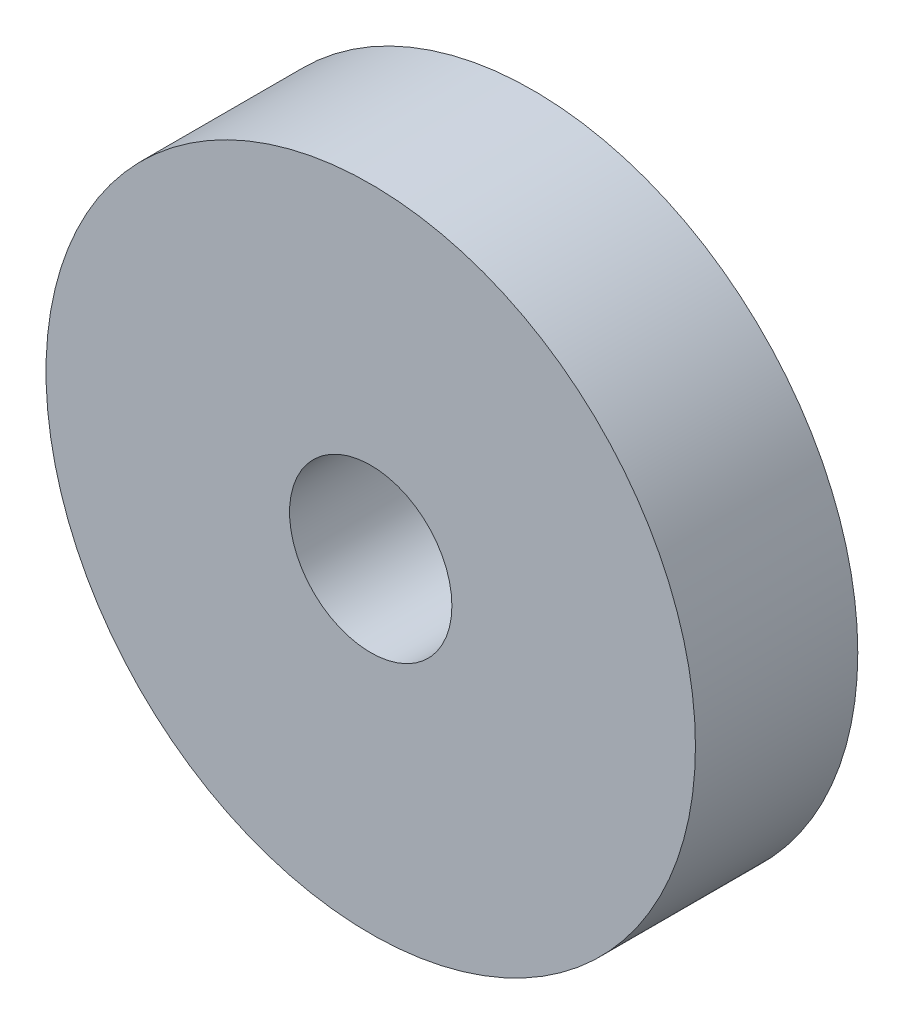
SolidWorks part; units mm, degrees
ref_plane "前视基准面" through (0, 0, 0) normal (0, 0, 1) x (1, 0, 0)
ref_plane "上视基准面" through (0, 0, 0) normal (0, 1, 0) x (1, 0, 0)
ref_plane "右视基准面" through (0, 0, 0) normal (1, 0, 0) x (0, 0, -1)
other "Configuration Table"
sketch "草图1" plane through (0, 0, 0) normal (0, 0, 1) x (1, 0, 0)
  circle A0 centre (0, 0) radius 10
  circle A1 centre (0, 0) radius 2.5
  dimension "D1" = 20
  dimension "D2" = 5
extrude "凸台-拉伸1" add sketch "草图1" along normal blind 5
